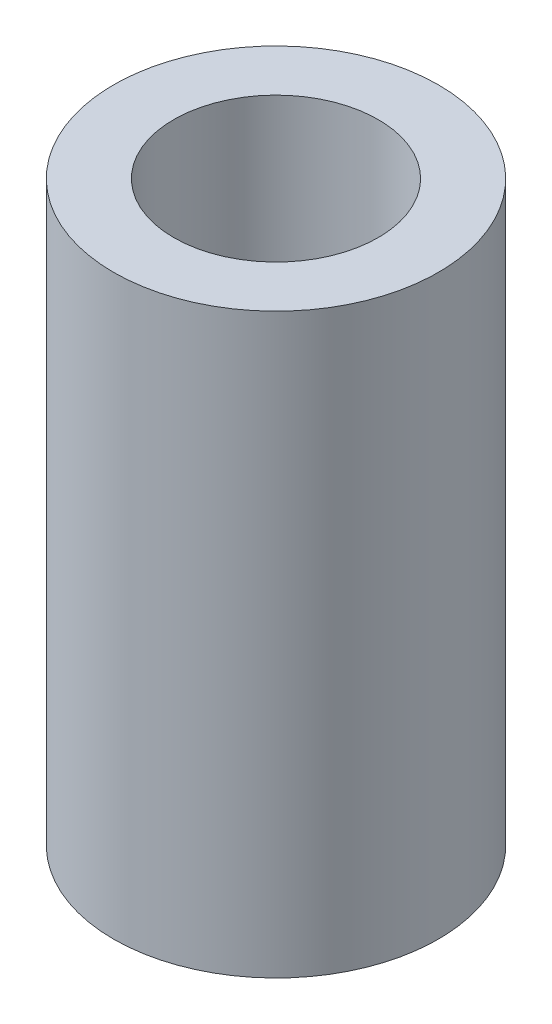
SolidWorks part; units mm, degrees
ref_plane "Front Plane" through (0, 0, 0) normal (0, 0, 1) x (1, 0, 0)
ref_plane "Top Plane" through (0, 0, 0) normal (0, 1, 0) x (1, 0, 0)
ref_plane "Right Plane" through (0, 0, 0) normal (1, 0, 0) x (0, 0, -1)
sketch "Sketch1" plane through (0, 0, 0) normal (0, 1, 0) x (1, 0, 0)
  circle A0 centre (0, 0) radius 6.75
  circle A1 centre (0, 0) radius 4.25
  dimension "D1" = 13.5
  dimension "D2" = 8.5
extrude "Boss-Extrude1" add sketch "Sketch1" along normal blind 24
